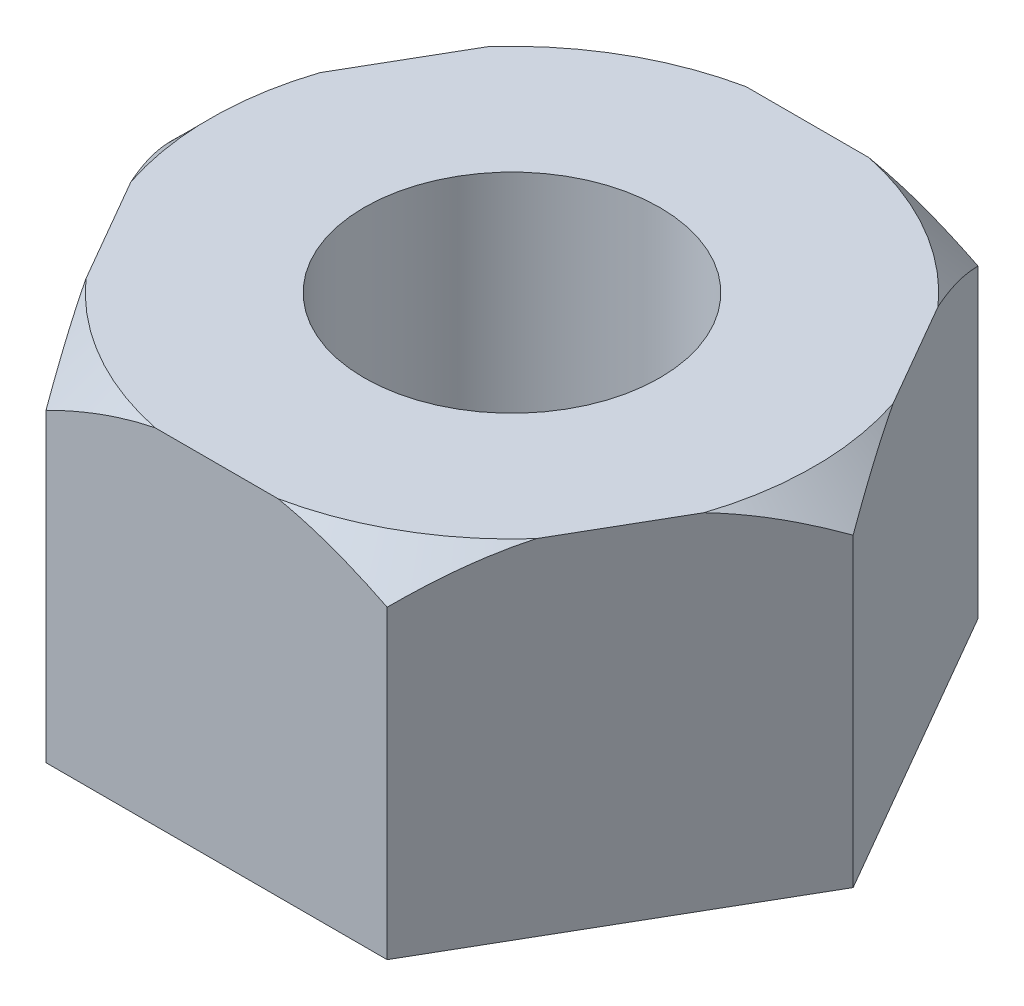
SolidWorks part; units mm, degrees
ref_plane "Front Plane" through (0, 0, 0) normal (0, 0, 1) x (1, 0, 0)
ref_plane "Top Plane" through (0, 0, 0) normal (0, 1, 0) x (1, 0, 0)
ref_plane "Right Plane" through (0, 0, 0) normal (1, 0, 0) x (0, 0, -1)
sketch "Sketch1" plane through (0, 0, 0) normal (0, 1, 0) x (1, 0, 0)
  line L0 (-34.641, 0) -> (34.641, 0)
  line L1 (17.3205, 30) -> (-17.3205, 30)
  line L2 (-17.3205, 30) -> (-34.641, 0)
  line L3 (-34.641, 0) -> (-17.3205, -30)
  line L4 (-17.3205, -30) -> (17.3205, -30)
  line L5 (17.3205, -30) -> (34.641, 0)
  line L6 (34.641, 0) -> (17.3205, 30)
  circle A0 centre (0, 0) radius 30 construction
  dimension "D1" = 60
extrude "Boss-Extrude1" add sketch "Sketch1" along normal blind 35 contours L4 L5 L0 L3 | L0 L6 L1 L2
sketch "Sketch6" plane through (0, 0, 0) normal (0, 0, 1) x (1, 0, 0)
  line L0 (30.641, 35) -> (34.641, 31)
  line L1 (17.3205, 35) -> (34.641, 35) construction
  line L4 (30.641, 35) -> (34.641, 35)
  line L5 (34.641, 35) -> (34.641, 31)
  line L6 (0, 42.4369) -> (0, 0)
  dimension "D1" = 4
revolve "Cut-Revolve2" cut sketch "Sketch6" angle 360 about L6
sketch "Sketch8" plane through (0, 0, 0) normal (0, -1, 0) x (-1, 0, 0)
  circle A0 centre (0, 0) radius 15
  dimension "D1" = 30
extrude "Cut-Extrude1" cut sketch "Sketch8" against normal through all
